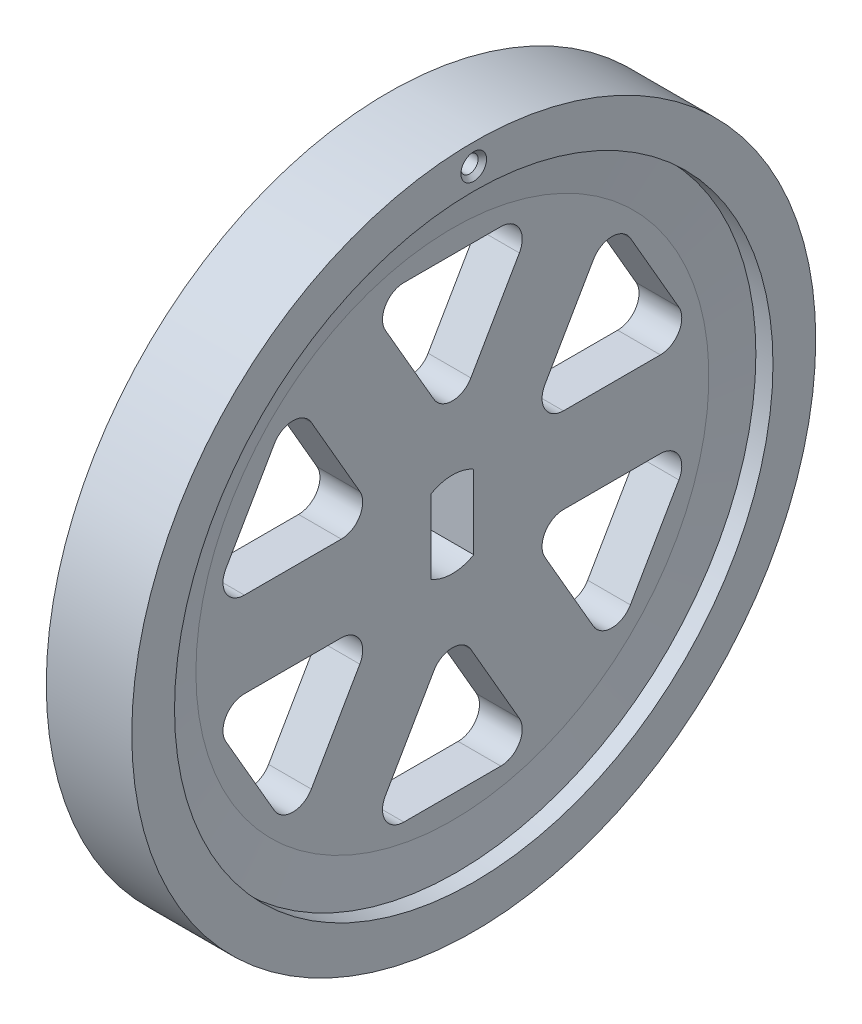
SolidWorks part; units mm, degrees
ref_plane "Front Plane" through (0, 0, 0) normal (0, 0, 1) x (1, 0, 0)
ref_plane "Top Plane" through (0, 0, 0) normal (0, 1, 0) x (1, 0, 0)
ref_plane "Right Plane" through (0, 0, 0) normal (1, 0, 0) x (0, 0, -1)
sketch "Sketch1" plane through (0, 0, 0) normal (0, 0, 1) x (1, 0, 0)
  line L0 (-6.35, 0) -> (6.35, 0)
  line L1 (6.35, 0) -> (6.35, 76.2)
  line L2 (6.35, 76.2) -> (7.62, 88.9)
  line L3 (7.62, 88.9) -> (12.7, 88.9)
  line L4 (12.7, 88.9) -> (12.7, 101.6)
  line L5 (12.7, 101.6) -> (-12.7, 101.6)
  line L6 (-12.7, 101.6) -> (-12.7, 88.9)
  line L7 (-12.7, 88.9) -> (-7.62, 88.9)
  line L8 (-7.62, 88.9) -> (-6.35, 76.2)
  line L9 (-6.35, 76.2) -> (-6.35, 0)
  line L10 (0, 0) -> (-21.2301, 0) construction
  line L11 (-21.2301, 0) -> (23.7925, 0) construction
  dimension "D1" = 12.7
  dimension "D2" = 13.97
  dimension "D3" = 19.05
  dimension "D4" = 13.97
  dimension "D5" = 19.05
  dimension "D6" = 6.35
  dimension "D7" = 203.2
  dimension "D8" = 177.8
  dimension "D9" = 152.4
revolve "Revolve1" add sketch "Sketch1" angle 360 about L11
sketch "Sketch2" plane through (6.35, 0, 0) normal (1, 0, 0) x (0, 0, -1)
  line L1 (5.4993, 34.925) -> (19.9007, 59.8691)
  line L2 (14.4015, 69.3941) -> (-14.4015, 69.3941)
  line L3 (-19.9007, 59.8691) -> (-5.4993, 34.925)
  circle A0 centre (0, 54.7294) radius 14.6647 construction
  arc A1 (-14.4015, 69.3941) -> (-19.9007, 59.8691) centre (-14.4015, 63.0441) ccw
  arc A2 (5.4993, 34.925) -> (-5.4993, 34.925) centre (0, 38.1) cw
  arc A3 (19.9007, 59.8691) -> (14.4015, 69.3941) centre (14.4015, 63.0441) ccw
  point P8 (-25.4, 69.3941)
  point P11 (0, 25.4)
  point P14 (25.4, 69.3941)
  dimension "D3" = 6.35
  dimension "D1" = 50.8
  dimension "D2" = 25.4
extrude "Cut-Extrude1" cut sketch "Sketch2" against normal through all
pattern_circular "CirPattern1" count 6 over 360 about axis through (0, 0, 0) along (1, 0, 0) of "Cut-Extrude1"
sketch "Sketch3" plane through (6.35, 0, 0) normal (1, 0, 0) x (0, 0, -1)
  line L0 (-6.35, 10.9985) -> (-6.35, -10.9985)
  line L1 (6.35, 10.9985) -> (6.35, -10.9985)
  arc A0 (-6.35, -10.9985) -> (6.35, -10.9985) centre (0, 0) ccw
  arc A1 (6.35, 10.9985) -> (-6.35, 10.9985) centre (0, 0) ccw
  dimension "D1" = 25.4
  dimension "D2" = 12.7
extrude "Cut-Extrude2" cut sketch "Sketch3" against normal through all
hole_wizard "1/4-20 Tapped Hole1" positions "Sketch6" profile "Sketch7" tap size "1/4-20" standard "ANSI Inch"
sketch "Sketch6" plane through (12.7, 0, 0) normal (1, 0, 0) x (0, 0, -1)
  point P0 (0, 95.25)
  dimension "D1" = 95.25
  dimension "D2" = 0
sketch "Sketch7" plane through (12.7, 95.25, 0) normal (0, 1, 0) x (0, 0, -1)
  line L0 (0, 0) -> (0, 14.2338)
  line L1 (0, 14.2338) -> (2.5527, 12.7)
  line L2 (2.5527, 12.7) -> (2.5527, 1.2573)
  line L3 (2.5527, 1.2573) -> (3.81, 0)
  line L5 (3.81, 0) -> (0, 0)
  line L6 (-2.5527, 1.2573) -> (-3.81, 0) construction
  line L10 (0, 14.2338) -> (-2.5527, 12.7) construction
  line L11 (0, -6.35) -> (0, 107.95) construction
  dimension "Tap Drill Dia." = 5.1054
  dimension "Tap Drill Depth" = 12.7
  dimension "Near C'Sink Dia." = 7.62
  dimension "Near C'Sink Angle" = 90
  dimension "Drill Angle" = 118
cosmetic thread "Hole Thread1" parameters "D1"=12.7, "D2"=6.35
equation "\"p\"=360"
